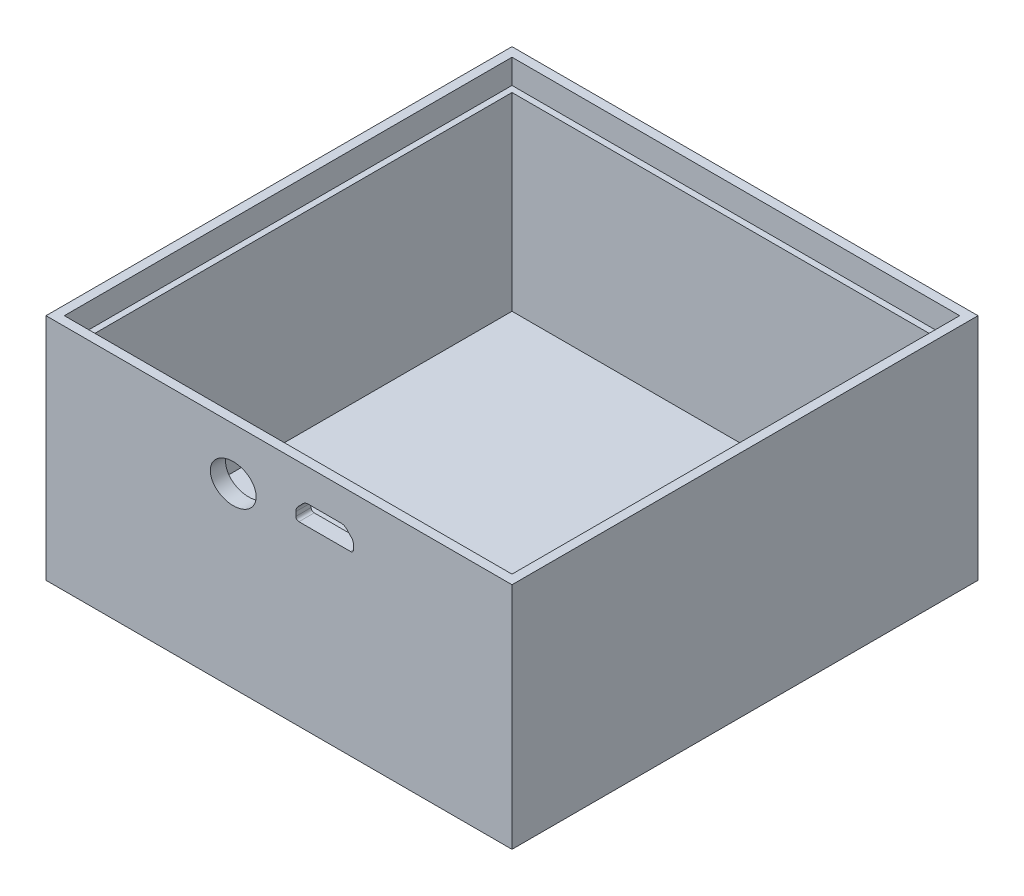
SolidWorks part; units mm, degrees
ref_plane "Front Plane" through (0, 0, 0) normal (0, 0, 1) x (1, 0, 0)
ref_plane "Top Plane" through (0, 0, 0) normal (0, 1, 0) x (1, 0, 0)
ref_plane "Right Plane" through (0, 0, 0) normal (1, 0, 0) x (0, 0, -1)
sketch "Sketch1" plane through (0, 0, 0) normal (0, 1, 0) x (1, 0, 0)
  line L1 (28.5, 0) -> (28.5, 57)
  line L2 (28.5, 57) -> (-28.5, 57)
  line L3 (-28.5, 57) -> (-28.5, 0)
  line L4 (-28.5, 0) -> (28.5, 0)
  line L6 (-30.5, 59) -> (30.5, 59)
  line L7 (30.5, 59) -> (30.5, -2)
  line L8 (30.5, -2) -> (-30.5, -2)
  line L9 (-30.5, -2) -> (-30.5, 59)
extrude "Boss-Extrude2" add sketch "Sketch1" along normal blind 30
sketch "Sketch2" plane through (0, 30, 0) normal (0, 1, 0) x (1, 0, 0)
  line L4 (-29.3, 57.8) -> (-29.3, -0.8)
  line L5 (-29.3, -0.8) -> (29.3, -0.8)
  line L6 (29.3, -0.8) -> (29.3, 57.8)
  line L7 (29.3, 57.8) -> (-29.3, 57.8)
extrude "Cut-Extrude1" cut sketch "Sketch2" against normal blind 3.2
sketch "Sketch4" plane through (0, 0, 0) normal (0, 0, -1) x (-1, 0, 0)
  line L0 (-28.5, 26.8) -> (0, 26.8)
  line L1 (28.5, 26.8) -> (-28.5, 26.8) construction
  line L3 (-5.9828, 25.8) -> (-5.9828, 23.2) construction
  line L4 (-2.6078, 23.2) -> (-9.3578, 23.2)
  line L5 (-9.7578, 23.6) -> (-9.7578, 24.1477)
  line L6 (-9.4792, 24.8402) -> (-8.8529, 25.4925)
  line L7 (-8.1316, 25.8) -> (-3.834, 25.8)
  line L8 (-2.4864, 24.8402) -> (-3.1126, 25.4925)
  line L9 (-2.2078, 23.6) -> (-2.2078, 24.1477)
  arc A0 (-8.8529, 25.4925) -> (-8.1316, 25.8) centre (-8.1316, 24.8) cw
  arc A1 (-3.1126, 25.4925) -> (-3.834, 25.8) centre (-3.834, 24.8) ccw
  arc A2 (-9.7578, 24.1477) -> (-9.4792, 24.8402) centre (-8.7578, 24.1477) cw
  arc A3 (-2.4864, 24.8402) -> (-2.2078, 24.1477) centre (-3.2078, 24.1477) cw
  arc A4 (-9.3578, 23.2) -> (-9.7578, 23.6) centre (-9.3578, 23.6) cw
  arc A5 (-2.2078, 23.6) -> (-2.6078, 23.2) centre (-2.6078, 23.6) cw
  ellipse E0 centre (5.9926, 23.2153) end of major axis (2.9926, 23.2153) minor radius 2.5
  ellipse E1 centre (5.9926, 23.2153) end of major axis (9.4679, 23.2307) minor radius 3
extrude "Cut-Extrude2" cut sketch "Sketch4" against normal through all contours L3 L7 A0 L6 A2 L5 A4 L4 | L7 L3 L4 A5 L9 A3 L8 A1 | E0
sketch "Sketch5" plane through (0, 0, 0) normal (0, -1, 0) x (1, 0, 0)
  line L0 (-28.5, 0) -> (28.5, 0)
  line L1 (28.5, 0) -> (28.5, -57)
  line L2 (28.5, -57) -> (-28.5, -57)
  line L3 (-28.5, -57) -> (-28.5, 0)
extrude "Boss-Extrude3" add sketch "Sketch5" against normal blind 2
